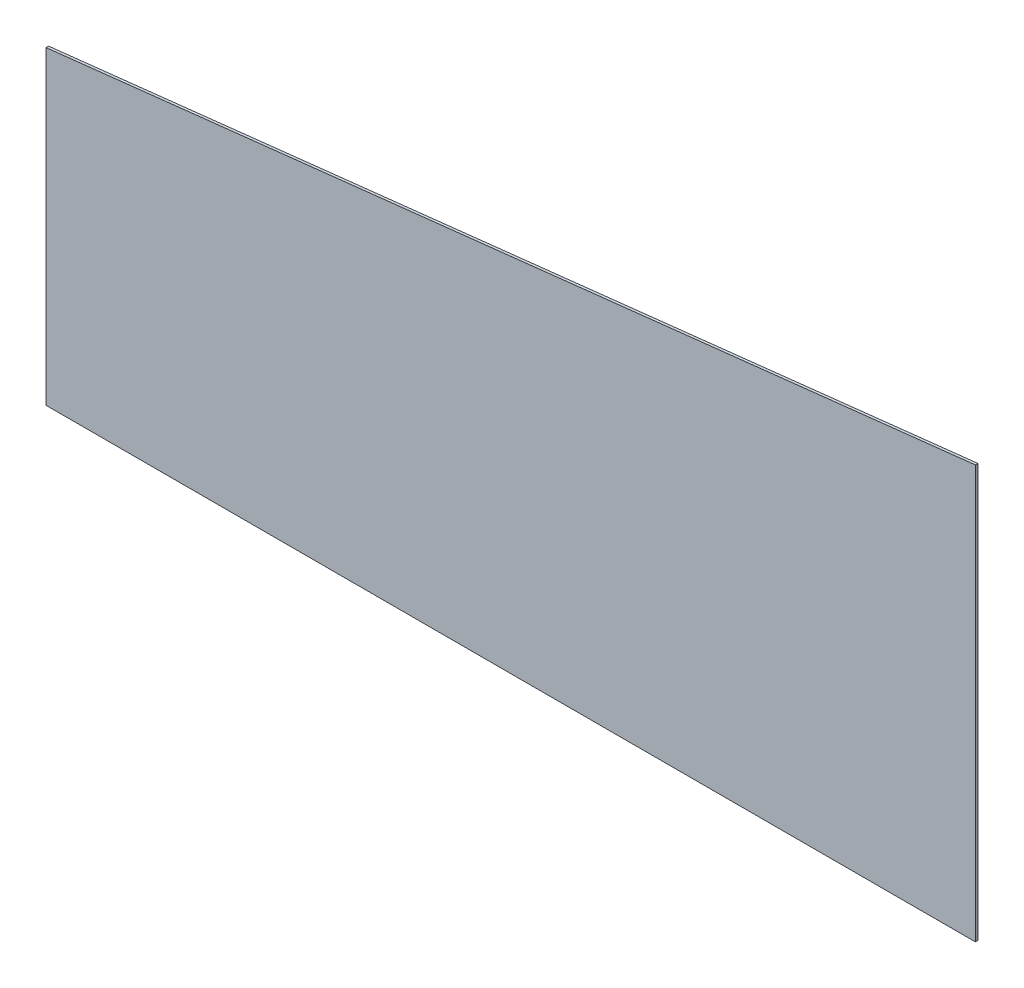
SolidWorks part; units mm, degrees
ref_plane "Front Plane" through (0, 0, 0) normal (0, 0, 1) x (1, 0, 0)
ref_plane "Top Plane" through (0, 0, 0) normal (0, 1, 0) x (1, 0, 0)
ref_plane "Right Plane" through (0, 0, 0) normal (1, 0, 0) x (0, 0, -1)
sketch "Sketch1" plane through (0, 0, 0) normal (0, 0, 1) x (1, 0, 0)
  line L0 (-900, 200) -> (900, 400)
  line L2 (-900, 200) -> (-900, -400)
  line L3 (-900, -400) -> (900, -400)
  line L4 (900, 400) -> (900, -400)
  line L5 (-900, 100) -> (900, 300) construction
  point P0 (0, 0)
  point P2 (-900, 100)
  point P6 (-900, 200)
  point P8 (900, 300)
  dimension "D1" = 1800
  dimension "D2" = 800
  dimension "D3" = 600
  dimension "D4" = 100
  dimension "D5" = 100
extrude "Boss-Extrude2" add sketch "Sketch1" along normal blind 5
